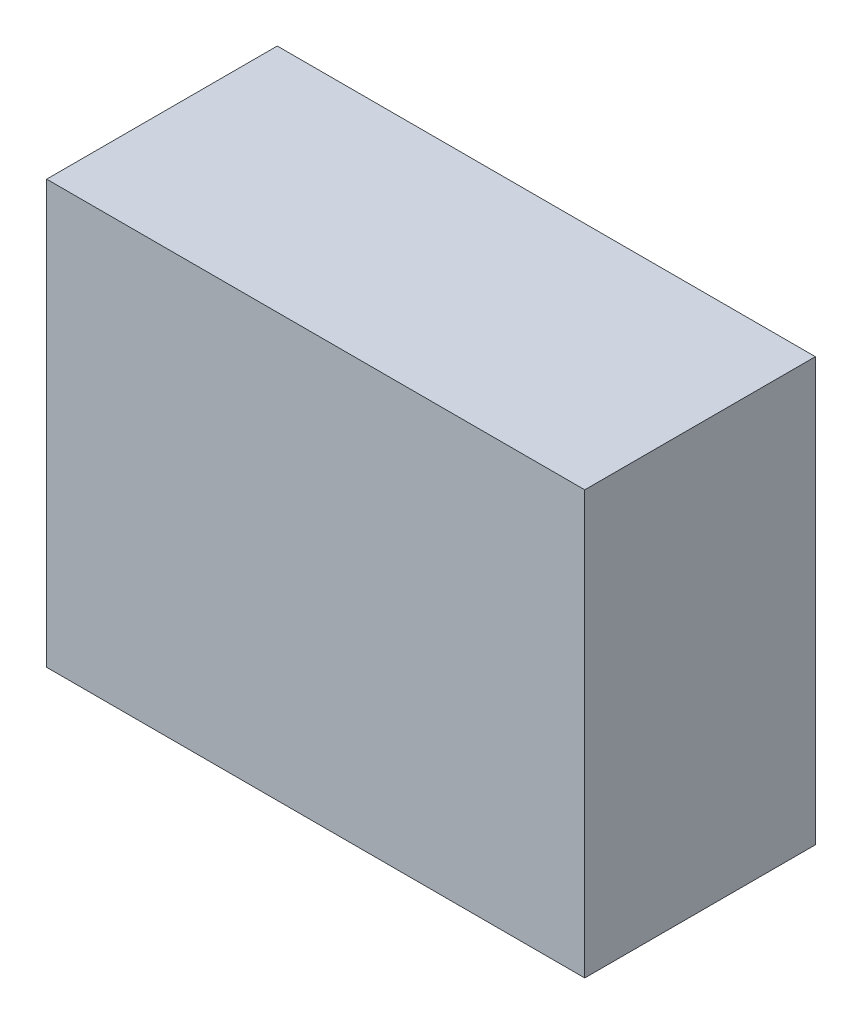
SolidWorks part; units mm, degrees
ref_plane "Front Plane" through (0, 0, 0) normal (0, 0, 1) x (1, 0, 0)
ref_plane "Top Plane" through (0, 0, 0) normal (0, 1, 0) x (1, 0, 0)
ref_plane "Right Plane" through (0, 0, 0) normal (1, 0, 0) x (0, 0, -1)
sketch "Sketch1" plane through (0, 0, 0) normal (0, 1, 0) x (1, 0, 0)
  line L1 (-45.8492, 33.7411) -> (131.9508, 33.7411)
  line L2 (-45.8492, 33.7411) -> (-45.8492, -42.4589)
  line L3 (-45.8492, -42.4589) -> (131.9508, -42.4589)
  line L4 (131.9508, 33.7411) -> (131.9508, -42.4589)
  dimension "D1" = 76.2
  dimension "D2" = 177.8
extrude "Boss-Extrude1" add sketch "Sketch1" along normal blind 139.7
